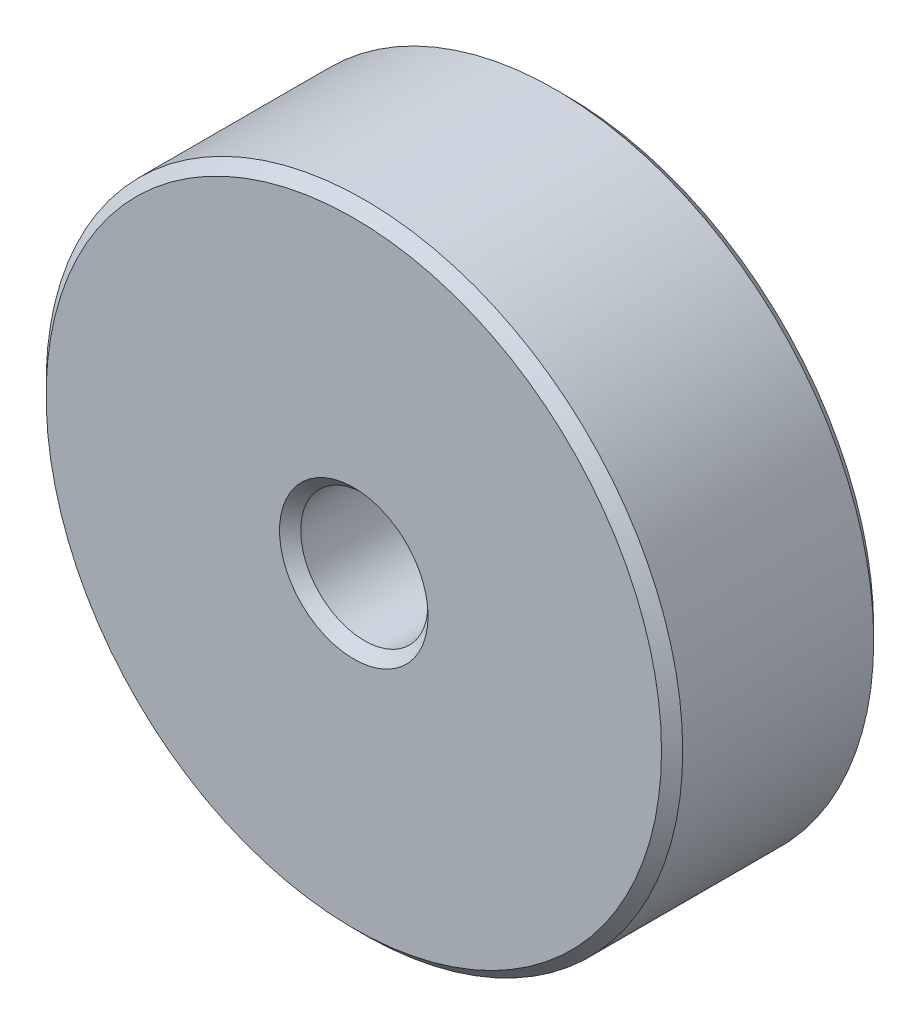
SolidWorks part; units mm, degrees
material "Nylon 101"
ref_plane "Front Plane" through (0, 0, 0) normal (0, 0, 1) x (1, 0, 0)
ref_plane "Top Plane" through (0, 0, 0) normal (0, 1, 0) x (1, 0, 0)
ref_plane "Right Plane" through (0, 0, 0) normal (1, 0, 0) x (0, 0, -1)
sketch "Sketch1" plane through (0, 0, 0) normal (0, 0, 1) x (1, 0, 0)
  circle A0 centre (0, 0) radius 15
  circle A1 centre (0, 0) radius 3
  dimension "D1" = 6
  dimension "D2" = 30
extrude "Boss-Extrude1" add sketch "Sketch1" along normal blind 10
chamfer "Chamfer1" distance 0.5 angle 45 4 edges at (3, 0, 0) (3, 0, 10) (15, 0, 0) (15, 0, 10)
